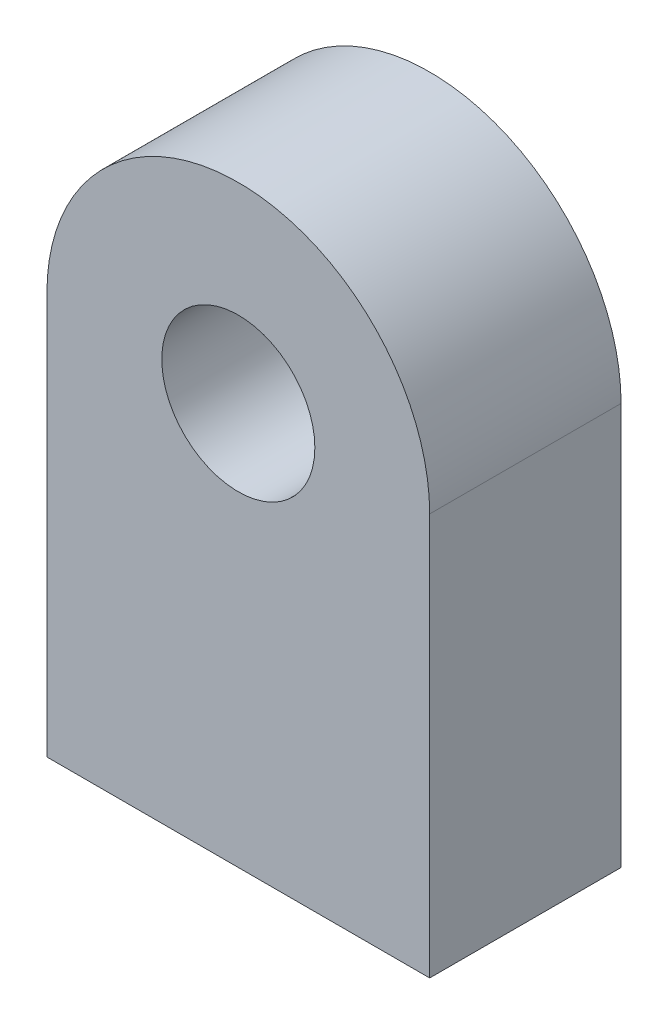
SolidWorks part; units mm, degrees
ref_plane "정면" through (0, 0, 0) normal (0, 0, 1) x (1, 0, 0)
ref_plane "윗면" through (0, 0, 0) normal (0, 1, 0) x (1, 0, 0)
ref_plane "우측면" through (0, 0, 0) normal (1, 0, 0) x (0, 0, -1)
sketch "스케치1" plane through (0, 0, 0) normal (0, 0, 1) x (1, 0, 0)
  line L0 (0, 0) -> (0, 21)
  line L2 (-10, 21) -> (10, 21)
  line L3 (-10, 21) -> (-10, 0)
  line L4 (-10, 0) -> (10, 0)
  line L5 (10, 21) -> (10, 0)
  circle A0 centre (0, 21) radius 4
  circle A1 centre (0, 21) radius 10
  dimension "D2" = 8
  dimension "D3" = 20
  dimension "D1" = 21
extrude "보스-돌출1" add sketch "스케치1" along normal blind 10 contours L2 A1 A0 | L2 A1 L0 A0 | L0 A1 L2 A0 | A1 L0 L4 L5 | A1 L3 L4 L0
